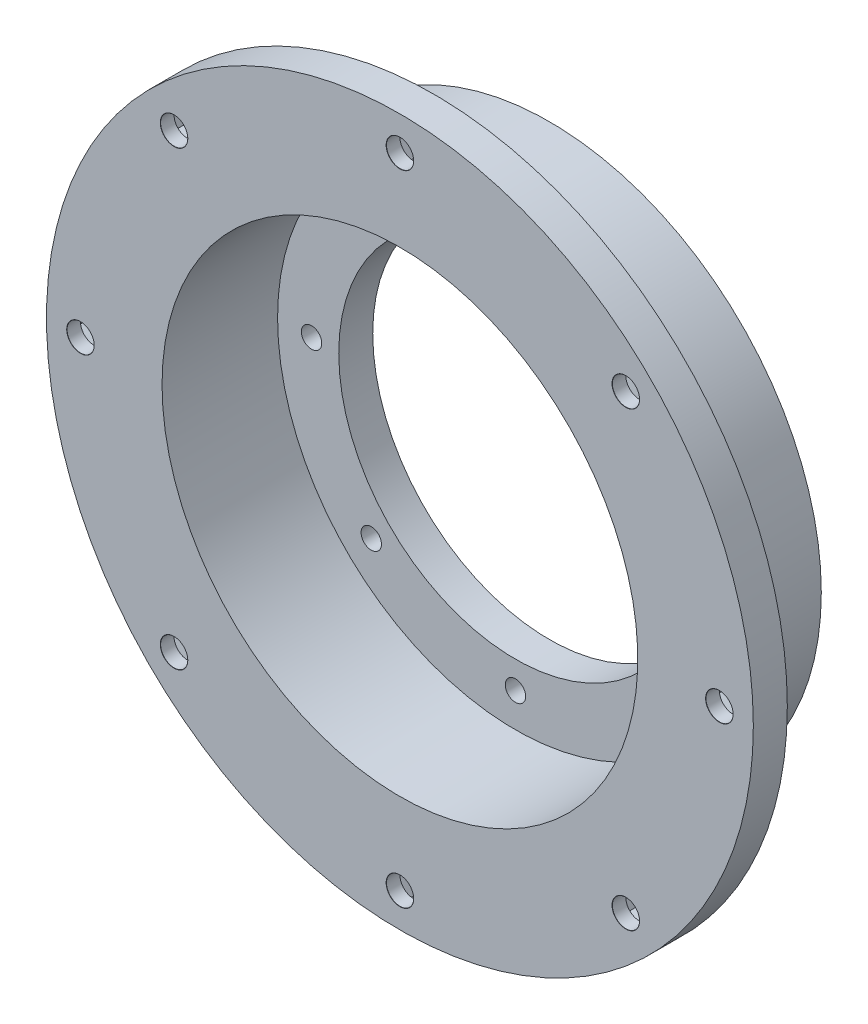
SolidWorks part; units mm, degrees
ref_plane "Front Plane" through (0, 0, 0) normal (0, 0, 1) x (1, 0, 0)
ref_plane "Top Plane" through (0, 0, 0) normal (0, 1, 0) x (1, 0, 0)
ref_plane "Right Plane" through (0, 0, 0) normal (1, 0, 0) x (0, 0, -1)
sketch "Sketch1" plane through (0, 0, 0) normal (0, 0, 1) x (1, 0, 0)
  line L0 (0, 0) -> (0, 63.1981) construction
  circle A0 centre (0, 0) radius 35
  circle A1 centre (0, 0) radius 26
  point P3 (0, 30)
  point P5 (21.2132, 21.2132)
  point P8 (30, 0)
  point P9 (21.2132, -21.2132)
  point P10 (0, -30)
  point P11 (-21.2132, -21.2132)
  point P12 (-30, 0)
  point P13 (-21.2132, 21.2132)
  point P14 (0, 0)
  dimension "D1" = 70
  dimension "D4" = 52
  dimension "D2" = 30
  dimension "D3" = 8
extrude "Boss-Extrude1" add sketch "Sketch1" along normal blind 5
sketch "Sketch2" plane through (0, 0, 0) normal (0, 0, 1) x (1, 0, 0)
  line L0 (0, 0) -> (0, 63.1981) construction
  circle A0 centre (0, 0) radius 45
  point P3 (0, 30)
  point P5 (21.2132, 21.2132)
  point P8 (30, 0)
  point P9 (21.2132, -21.2132)
  point P10 (0, -30)
  point P11 (-21.2132, -21.2132)
  point P12 (-30, 0)
  point P13 (-21.2132, 21.2132)
  point P14 (0, 0)
  dimension "D1" = 90
  dimension "D2" = 30
  dimension "D3" = 8
hole_wizard "Ø3.0mm Dowel Hole1" positions "Sketch3" profile "Sketch4" hole size "Ø3.0" standard "ISO" end condition through all
sketch "Sketch3" plane through (0, 0, 0) normal (0, 0, -1) x (-1, 0, 0)
  point P0 (21.2132, 21.2132)
  point P3 (0, 30)
  point P6 (-21.2132, 21.2132)
  point P9 (-30, 0)
  point P12 (-21.2132, -21.2132)
  point P15 (0, -30)
  point P18 (21.2132, -21.2132)
  point P21 (30, 0)
sketch "Sketch4" plane through (-21.2132, 21.2132, 0) normal (1, 0, 0) x (0, 1, 0)
  line L0 (0, 0) -> (0, 5)
  line L1 (0, 5) -> (1.5, 5)
  line L2 (1.5, 5) -> (1.5, 0.025)
  line L3 (1.5, 0.025) -> (1.525, 0)
  line L5 (1.525, 0) -> (0, 0)
  line L6 (-1.5, 0.025) -> (-1.525, 0) construction
  line L11 (0, -6.35) -> (0, 107.95) construction
  dimension "Thru Hole Dia." = 3
  dimension "Thru Hole Depth" = 5
  dimension "Near C'Sink Dia." = 3.05
  dimension "Near C'Sink Angle" = 90
ref_plane "Plane1" through (0, 0, 0) normal (0, 0, -1) x (-1, 0, 0)
sketch "Sketch5" plane through (0, 0, 0) normal (0, 0, -1) x (-1, 0, 0)
  circle A0 centre (0, 0) radius 40
  circle A1 centre (0, 0) radius 35
  dimension "D1" = 80
extrude "Boss-Extrude2" add sketch "Sketch5" against normal blind 22 contours A0 A1
ref_plane "Plane2" through (0, 0, 22) normal (0, 0, 1) x (1, 0, 0)
sketch "Sketch6" plane through (0, 0, 22) normal (0, 0, 1) x (1, 0, 0)
  circle A0 centre (0, 0) radius 52
  circle A1 centre (0, 0) radius 35
  dimension "D1" = 104
extrude "Boss-Extrude3" add sketch "Sketch6" against normal blind 5
sketch "Sketch7" plane through (0, 0, 22) normal (0, 0, 1) x (1, 0, 0)
  line L0 (0, 0) -> (0, 63.1981) construction
  circle A0 centre (0, 0) radius 45
  point P3 (0, 47)
  point P5 (33.234, 33.234)
  point P8 (47, 0)
  point P9 (33.234, -33.234)
  point P10 (0, -47)
  point P11 (-33.234, -33.234)
  point P12 (-47, 0)
  point P13 (-33.234, 33.234)
  point P14 (0, 0)
  dimension "D1" = 90
  dimension "D2" = 47
  dimension "D3" = 8
hole_wizard "Ø4.0mm Dowel Hole2" positions "Sketch8" profile "Sketch9" hole size "Ø4.0" standard "ISO" end condition through all
sketch "Sketch8" plane through (0, 0, 22) normal (0, 0, 1) x (1, 0, 0)
  point P0 (0, 47)
  point P3 (-33.234, 33.234)
  point P6 (-47, 0)
  point P9 (-33.234, -33.234)
  point P12 (0, -47)
  point P15 (33.234, -33.234)
  point P18 (47, 0)
  point P21 (33.234, 33.234)
sketch "Sketch9" plane through (0, 47, 22) normal (1, 0, 0) x (0, -1, 0)
  line L0 (0, 0) -> (0, 22)
  line L1 (0, 22) -> (2, 22)
  line L2 (2, 22) -> (2, 0.025)
  line L3 (2, 0.025) -> (2.025, 0)
  line L5 (2.025, 0) -> (0, 0)
  line L6 (-2, 0.025) -> (-2.025, 0) construction
  line L11 (0, -6.35) -> (0, 107.95) construction
  dimension "Thru Hole Dia." = 4
  dimension "Thru Hole Depth" = 22
  dimension "Near C'Sink Dia." = 4.05
  dimension "Near C'Sink Angle" = 90
ref_plane "Plane3" through (0, 0, 17) normal (0, 0, -1) x (-1, 0, 0)
sketch "Sketch10" plane through (0, 0, 17) normal (0, 0, -1) x (-1, 0, 0)
  line L0 (0, 0) -> (0, 63.1981) construction
  line L1 (36.5, 29.968) -> (37.6954, 34.4295)
  line L2 (4.6188, 47) -> (2.3094, 51)
  line L3 (2.3094, 51) -> (-2.3094, 51)
  line L4 (-2.3094, 51) -> (-4.6188, 47)
  line L5 (-4.6188, 47) -> (-2.3094, 43)
  line L6 (-2.3094, 43) -> (2.3094, 43)
  line L7 (2.3094, 43) -> (4.6188, 47)
  line L8 (37.6954, 34.4295) -> (34.4295, 37.6954)
  line L9 (34.4295, 37.6954) -> (29.968, 36.5)
  line L10 (29.968, 36.5) -> (28.7726, 32.0386)
  line L11 (28.7726, 32.0386) -> (32.0386, 28.7726)
  line L12 (32.0386, 28.7726) -> (36.5, 29.968)
  line L13 (47, -4.6188) -> (51, -2.3094)
  line L14 (51, -2.3094) -> (51, 2.3094)
  line L15 (51, 2.3094) -> (47, 4.6188)
  line L16 (47, 4.6188) -> (43, 2.3094)
  line L17 (43, 2.3094) -> (43, -2.3094)
  line L18 (43, -2.3094) -> (47, -4.6188)
  line L19 (29.968, -36.5) -> (34.4295, -37.6954)
  line L20 (34.4295, -37.6954) -> (37.6954, -34.4295)
  line L21 (37.6954, -34.4295) -> (36.5, -29.968)
  line L22 (36.5, -29.968) -> (32.0386, -28.7726)
  line L23 (32.0386, -28.7726) -> (28.7726, -32.0386)
  line L24 (28.7726, -32.0386) -> (29.968, -36.5)
  line L25 (-4.6188, -47) -> (-2.3094, -51)
  line L26 (-2.3094, -51) -> (2.3094, -51)
  line L27 (2.3094, -51) -> (4.6188, -47)
  line L28 (4.6188, -47) -> (2.3094, -43)
  line L29 (2.3094, -43) -> (-2.3094, -43)
  line L30 (-2.3094, -43) -> (-4.6188, -47)
  line L31 (-36.5, -29.968) -> (-37.6954, -34.4295)
  line L32 (-37.6954, -34.4295) -> (-34.4295, -37.6954)
  line L33 (-34.4295, -37.6954) -> (-29.968, -36.5)
  line L34 (-29.968, -36.5) -> (-28.7726, -32.0386)
  line L35 (-28.7726, -32.0386) -> (-32.0386, -28.7726)
  line L36 (-32.0386, -28.7726) -> (-36.5, -29.968)
  line L37 (-47, 4.6188) -> (-51, 2.3094)
  line L38 (-51, 2.3094) -> (-51, -2.3094)
  line L39 (-51, -2.3094) -> (-47, -4.6188)
  line L40 (-47, -4.6188) -> (-43, -2.3094)
  line L41 (-43, -2.3094) -> (-43, 2.3094)
  line L42 (-43, 2.3094) -> (-47, 4.6188)
  line L43 (-29.968, 36.5) -> (-34.4295, 37.6954)
  line L44 (-34.4295, 37.6954) -> (-37.6954, 34.4295)
  line L45 (-37.6954, 34.4295) -> (-36.5, 29.968)
  line L46 (-36.5, 29.968) -> (-32.0386, 28.7726)
  line L47 (-32.0386, 28.7726) -> (-28.7726, 32.0386)
  line L48 (-28.7726, 32.0386) -> (-29.968, 36.5)
  circle A1 centre (0, 47) radius 4 construction
  point P3 (0, 47)
  point P5 (33.234, 33.234)
  point P8 (47, 0)
  point P9 (33.234, -33.234)
  point P10 (0, -47)
  point P11 (-33.234, -33.234)
  point P12 (-47, 0)
  point P13 (-33.234, 33.234)
  point P14 (0, 0)
  point P64 (0, 0)
  dimension "D1" = 8
  dimension "D2" = 47
  dimension "D3" = 8
extrude "Cut-Extrude1" cut sketch "Sketch10" against normal blind 3
